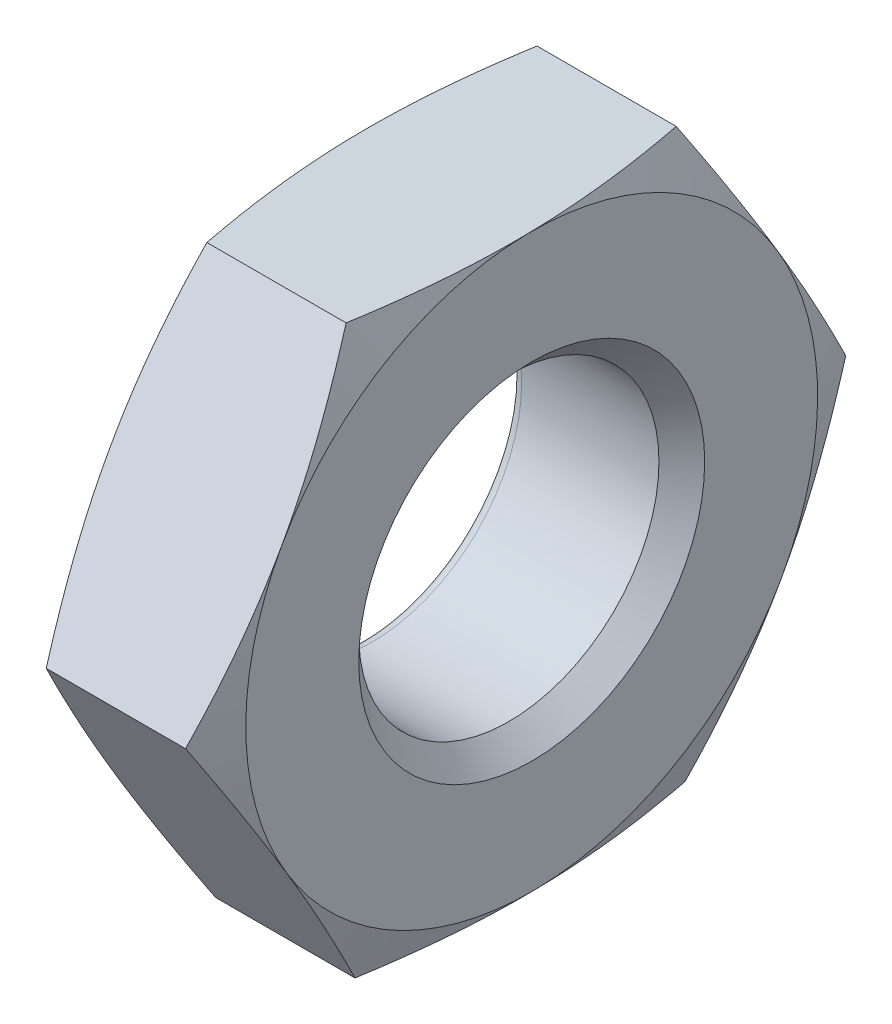
SolidWorks part; units mm, degrees
material "AISI 1020"
ref_plane "Plano superior" through (0, 0, 0) normal (0, 0, 1) x (1, 0, 0)
ref_plane "Plano frontal" through (0, 0, 0) normal (0, 1, 0) x (1, 0, 0)
ref_plane "Plano direito" through (0, 0, 0) normal (1, 0, 0) x (0, 0, -1)
sketch "Esboço1" plane through (0, 0, 0) normal (1, 0, 0) x (0, 0, -1)
  line L1 (2.8087, 5.0442) -> (-2.9641, 4.9545)
  line L2 (-2.9641, 4.9545) -> (-5.7728, -0.0897)
  line L3 (-5.7728, -0.0897) -> (-2.8087, -5.0442)
  line L4 (-2.8087, -5.0442) -> (2.9641, -4.9545)
  line L5 (2.9641, -4.9545) -> (5.7728, 0.0897)
  line L6 (5.7728, 0.0897) -> (2.8087, 5.0442)
  circle A0 centre (0, 0) radius 5 construction
  dimension "D1" = 10
extrude "Ressalto-extrusão1" add sketch "Esboço1" along normal blind 3
hole_wizard "Furo roscado de M6x0.752" positions "Esboço10" profile "Esboço11" tap size "M6x0.75" standard "DIN" end condition up to next
sketch "Esboço10" plane through (3, 0, 0) normal (1, 0, 0) x (0, 0, -1)
  point P0 (0, 0)
sketch "Esboço11" plane through (3, 0, 0) normal (0, 1, 0) x (0, 0, -1)
  line L0 (0, 0) -> (0, 3)
  line L1 (0, 3) -> (2.625, 3)
  line L2 (2.625, 3) -> (2.625, 0.4)
  line L3 (2.625, 0.4) -> (3.025, 0)
  line L5 (3.025, 0) -> (0, 0)
  line L6 (-2.625, 0.4) -> (-3.025, 0) construction
  line L11 (0, -6.35) -> (0, 107.95) construction
  dimension "Thru Tap Drill Dia." = 5.25
  dimension "Thru Tap Drill Depth" = 3
  dimension "Near C'Sink Dia." = 6.05
  dimension "Near C'Sink Angle" = 90
cosmetic thread "Rosca de furo1" parameters "D2"=6
cosmetic thread "Representação de rosca1" parameters "D2"=5.838
fillet "Filete1" radius 0.2 1 edges at (0, 0, -2.625)
sketch "Esboço12" plane through (3, 0, 0) normal (1, 0, 0) x (0, 0, -1)
  circle A0 centre (0, 0) radius 5
extrude "Corte-extrusão3" cut sketch "Esboço12" against normal blind 13 draft 70 flip side to cut contours A0
sketch "Esboço17" plane through (0, 0, 0) normal (-1, 0, 0) x (0, 0, 1)
  circle A0 centre (0, 0) radius 4.9945
extrude "Corte-extrusão4" cut sketch "Esboço17" against normal blind 13 draft 70 flip side to cut
